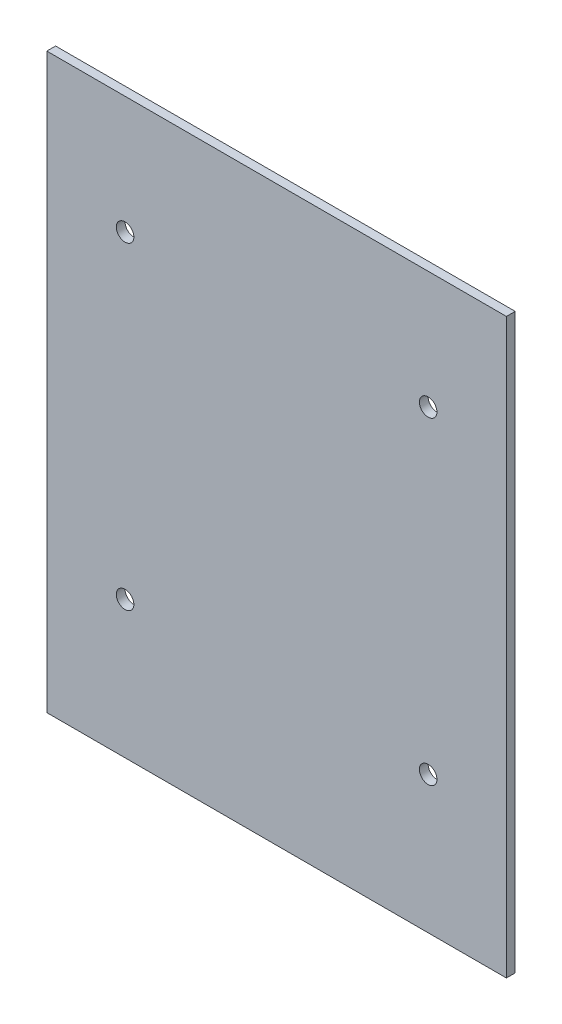
SolidWorks part; units mm, degrees
material "Acrylic (Medium-high impact)"
ref_plane "Front Plane" through (0, 0, 0) normal (0, 0, 1) x (1, 0, 0)
ref_plane "Top Plane" through (0, 0, 0) normal (0, 1, 0) x (1, 0, 0)
ref_plane "Right Plane" through (0, 0, 0) normal (1, 0, 0) x (0, 0, -1)
sketch "Sketch1" plane through (0, 0, 0) normal (0, 0, 1) x (1, 0, 0)
  line L0 (0, 0) -> (166.124, 0)
  line L2 (0, 0) -> (0, -207.09)
  line L3 (0, -207.09) -> (166.124, -207.09)
  line L4 (166.124, 0) -> (166.124, -207.09)
  line L5 (83.062, 0) -> (83.062, -207.09) construction
  line L6 (28.287, -42.5) -> (137.837, -42.5) construction
  line L7 (28.287, -42.5) -> (28.287, -157.5) construction
  line L8 (28.287, -157.5) -> (137.837, -157.5) construction
  line L9 (137.837, -42.5) -> (137.837, -157.5) construction
  circle A0 centre (28.287, -42.5) radius 3.175
  circle A1 centre (137.837, -42.5) radius 3.175
  circle A2 centre (28.287, -157.5) radius 3.175
  circle A3 centre (137.837, -157.5) radius 3.175
  dimension "D5" = 6.35
  dimension "D6" = 6.35
  dimension "D7" = 6.35
  dimension "D8" = 6.35
  dimension "D1" = 166.124
  dimension "D2" = 207.09
  dimension "D3" = 109.55
  dimension "D4" = 115
  dimension "D9" = 54.775
  dimension "D10" = 42.5
extrude "Boss-Extrude1" add sketch "Sketch1" along normal blind 3.175
